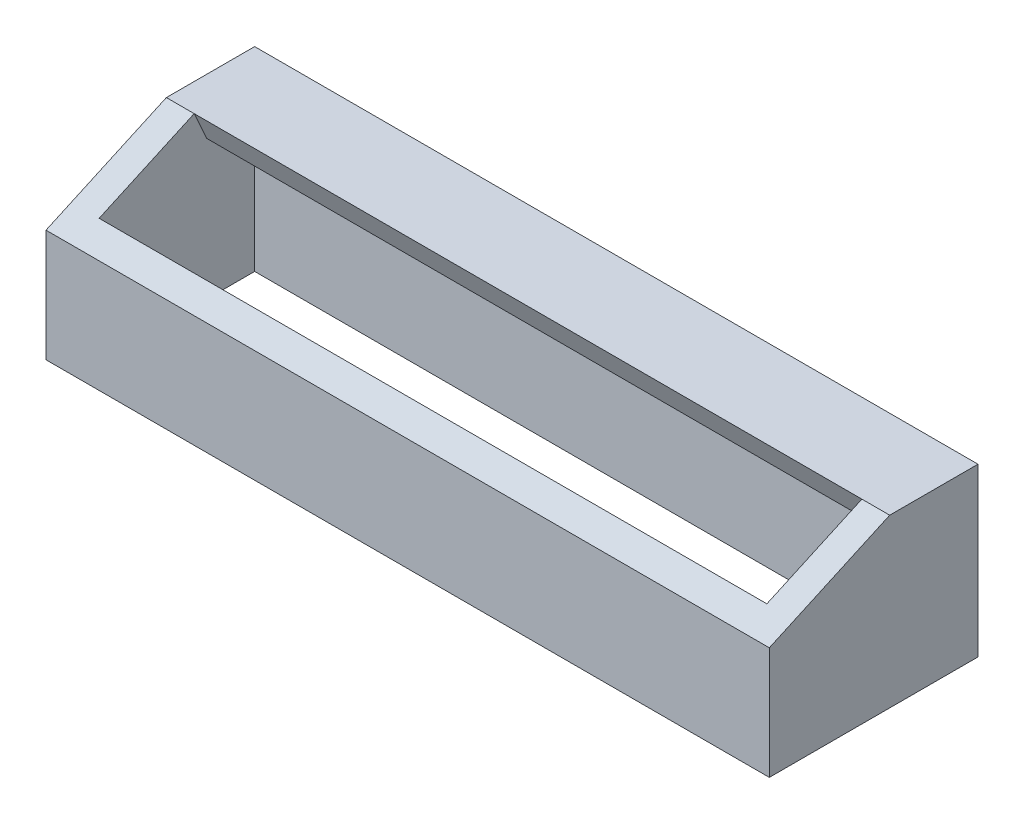
SolidWorks part; units mm, degrees
ref_plane "前基準面" through (0, 0, 0) normal (0, 0, 1) x (1, 0, 0)
ref_plane "上基準面" through (0, 0, 0) normal (0, 1, 0) x (1, 0, 0)
ref_plane "右基準面" through (0, 0, 0) normal (1, 0, 0) x (0, 0, -1)
sketch "草圖1" plane through (0, 0, 0) normal (0, 1, 0) x (1, 0, 0)
  line L1 (-260, 75) -> (260, 75)
  line L2 (-260, 75) -> (-260, -75)
  line L3 (-260, -75) -> (260, -75)
  line L4 (260, 75) -> (260, -75)
  line L5 (-260, 75) -> (260, -75) construction
  line L6 (-260, -75) -> (260, 75) construction
  point P0 (0, 0)
  dimension "D1" = 520
  dimension "D2" = 150
extrude "填料-伸長1" add sketch "草圖1" along normal blind 80
sketch "草圖3" plane through (0, 80, 0) normal (0, 1, 0) x (1, 0, 0)
  line L1 (-260, 75) -> (260, 75)
  line L2 (-260, 75) -> (-260, -75)
  line L3 (-260, -75) -> (260, -75)
  line L4 (260, 75) -> (260, -75)
extrude "填料-伸長2" add sketch "草圖3" along normal blind 40
sketch "草圖4" plane through (260, 0, 0) normal (1, 0, 0) x (0, 0, -1)
  line L0 (-75, 80.7066) -> (11.5244, 120)
  line L1 (-75, 120) -> (-75, 0) construction
  line L2 (-75, 120) -> (75, 120) construction
  line L3 (11.5244, 120) -> (-75, 120)
  line L4 (-75, 120) -> (-75, 80.7066)
extrude "除料-伸長1" cut sketch "草圖4" against normal through all
sketch "草圖5" plane through (0, 0, 0) normal (0, -1, 0) x (-1, 0, 0)
  line L0 (260, -75) -> (-260, -75) construction
  line L1 (240, -55) -> (-240, -55)
  line L2 (240, -55) -> (240, 55)
  line L3 (240, 55) -> (-240, 55)
  line L4 (-240, -55) -> (-240, 55)
  line L5 (240, -55) -> (-240, 55) construction
  line L6 (240, 55) -> (-240, -55) construction
  line L7 (260, 75) -> (260, -75) construction
  point P0 (0, 0)
  dimension "D1" = 20
  dimension "D2" = 20
extrude "除料-伸長2" cut sketch "草圖5" against normal blind 70
sketch "草圖7" plane through (0, 95.1444, 43.208) normal (0, 0.9105, 0.4135) x (1, 0, 0)
  line L0 (-260, 60.1118) -> (260, 60.1118) construction
  line L1 (-240, 40.1118) -> (240, 40.1118)
  line L2 (-240, 40.1118) -> (-240, -14.9168)
  line L3 (-240, -14.9168) -> (240, -14.9168)
  line L4 (240, 40.1118) -> (240, -14.9168)
  line L5 (-260, -34.9168) -> (260, -34.9168) construction
  line L6 (-260, -34.9168) -> (-260, 60.1118) construction
  line L7 (260, -34.9168) -> (260, 60.1118) construction
  dimension "D1" = 20
  dimension "D2" = 20
  dimension "D3" = 20
  dimension "D4" = 20
extrude "除料-伸長3" cut sketch "草圖7" against normal blind 70
ref_plane "平面1" through (0, 0, -85) normal (0, 0, -1) x (-1, 0, 0)
sketch "草圖8" plane through (0, 70, 0) normal (0, -1, 0) x (1, 0, 0)
  line L1 (240, -55) -> (-240, -55)
  line L2 (240, -55) -> (240, -12.2652)
  line L3 (240, -12.2652) -> (-240, -12.2652)
  line L4 (-240, -55) -> (-240, -12.2652)
extrude "除料-伸長5" cut sketch "草圖8" against normal blind 30
sketch "草圖9" plane through (0, 16.5858, -36.5222) normal (0, -0.4135, 0.9105) x (1, 0, 0)
  line L0 (-240, 58.6641) -> (240, 58.6641) construction
  line L1 (-240, 104.4958) -> (240, 104.4958)
  line L2 (-240, 104.4958) -> (-240, 58.6641)
  line L3 (-240, 58.6641) -> (240, 58.6641)
  line L4 (240, 104.4958) -> (240, 58.6641)
extrude "除料-伸長6" cut sketch "草圖9" against normal blind 20
sketch "草圖10" plane through (0, 0, -85) normal (0, 0, -1) x (-1, 0, 0)
  line L0 (-260, 120) -> (-260, 0) construction
  line L1 (-200, 20) -> (-175, 20)
  line L2 (-200, 20) -> (-200, 0)
  line L3 (-200, 0) -> (-175, 0)
  line L4 (-175, 20) -> (-175, 0)
  line L5 (-260, 0) -> (260, 0) construction
  dimension "D1" = 60
  dimension "D2" = 0
  dimension "D3" = 20
  dimension "D4" = 25
extrude "填料-伸長3" add sketch "草圖10" against normal blind 20
sketch "草圖11" plane through (0, 0, -85) normal (0, 0, -1) x (-1, 0, 0)
  line L0 (260, 120) -> (260, 0) construction
  line L1 (175, 20) -> (200, 20)
  line L2 (175, 20) -> (175, 0)
  line L3 (175, 0) -> (200, 0)
  line L4 (200, 20) -> (200, 0)
  line L5 (-175, 0) -> (260, 0) construction
  dimension "D1" = 60
  dimension "D2" = 20
  dimension "D3" = 25
  dimension "D4" = 0
extrude "填料-伸長4" add sketch "草圖11" against normal blind 20
